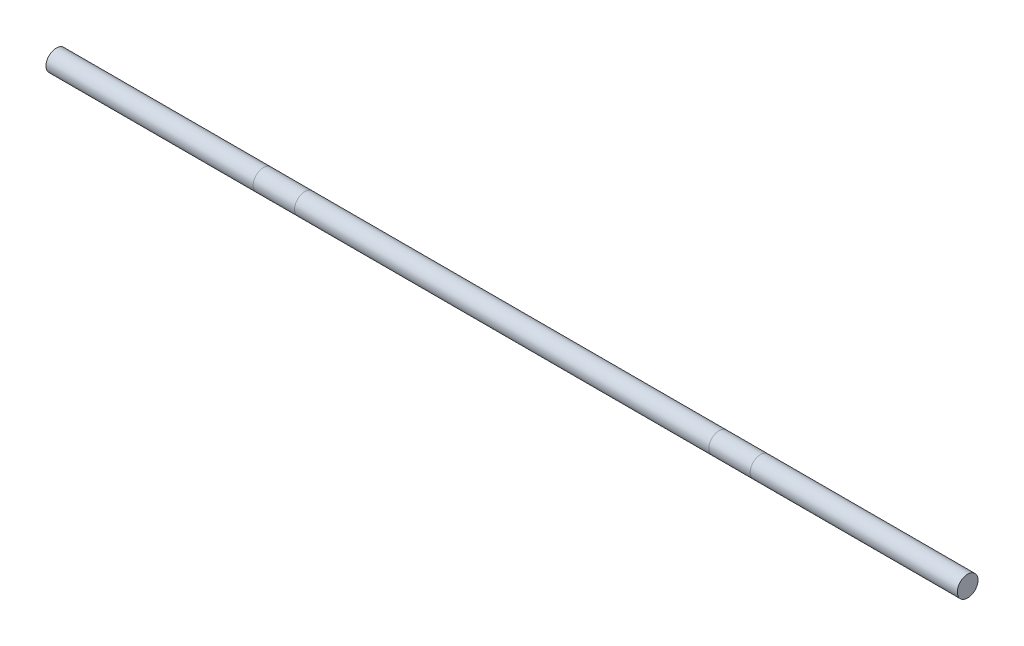
SolidWorks part; units mm, degrees
material "黄铜"
ref_plane "前视基准面" through (0, 0, 0) normal (0, 0, 1) x (1, 0, 0)
ref_plane "上视基准面" through (0, 0, 0) normal (0, 1, 0) x (1, 0, 0)
ref_plane "右视基准面" through (0, 0, 0) normal (1, 0, 0) x (0, 0, -1)
sketch "草图1" plane through (0, 0, 0) normal (1, 0, 0) x (0, 0, -1)
  circle A0 centre (0, 0) radius 25
  dimension "D1" = 50
extrude "凸台-拉伸1" add sketch "草图1" along normal mid plane 2200
sketch "草图2" plane through (0, 0, 0) normal (0, 0, 1) x (1, 0, 0)
  line L0 (0, 0) -> (0, 332.5658) construction
  line L1 (-600, 160.8409) -> (-500, 160.8409)
  line L2 (-600, 160.8409) -> (-600, -156.0036)
  line L3 (-600, -156.0036) -> (-500, -156.0036)
  line L4 (-500, 160.8409) -> (-500, -156.0036)
  line L5 (500, 160.8409) -> (500, -156.0036)
  line L6 (600, -156.0036) -> (500, -156.0036)
  line L7 (600, 160.8409) -> (600, -156.0036)
  line L8 (600, 160.8409) -> (500, 160.8409)
  dimension "D1" = 100
  dimension "D2" = 1000
split line "分割线2"
